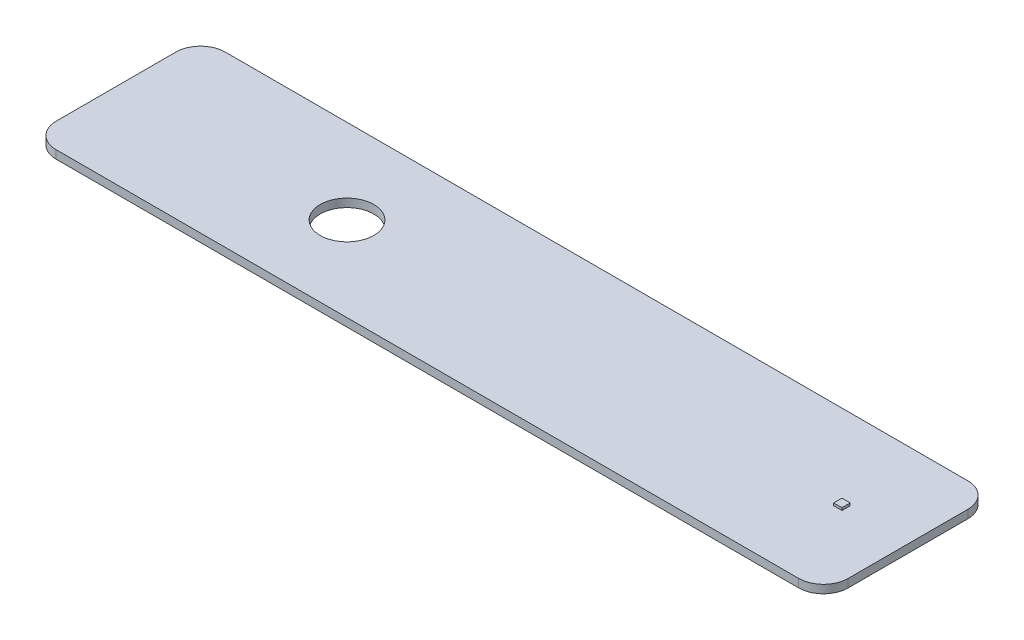
SolidWorks part; units mm, degrees
other "Markup1"
sketch "Sketch4" plane through (-48, 1.9, -10.25) normal (0, 1, 0) x (1, 0, 0)
material "Custom Plastic"
ref_plane "Front Plane" through (0, 0, 0) normal (0, 0, 1) x (1, 0, 0)
ref_plane "Top Plane" through (0, 0, 0) normal (0, 1, 0) x (1, 0, 0)
ref_plane "Right Plane" through (0, 0, 0) normal (1, 0, 0) x (0, 0, -1)
sketch "Sketch1" plane through (0, 0, 0) normal (0, 1, 0) x (1, 0, 0)
  line L1 (-45, 10.25) -> (45, 10.25)
  line L2 (-48, 7.25) -> (-48, -7.25)
  line L3 (-45, -10.25) -> (45, -10.25)
  line L4 (48, 7.25) -> (48, -7.25)
  line L5 (-48, 10.25) -> (48, -10.25) construction
  line L6 (-48, -10.25) -> (48, 10.25) construction
  arc A0 (-48, -7.25) -> (-45, -10.25) centre (-45, -7.25) ccw
  arc A1 (45, -10.25) -> (48, -7.25) centre (45, -7.25) ccw
  arc A2 (45, 10.25) -> (48, 7.25) centre (45, 7.25) cw
  arc A3 (-45, 10.25) -> (-48, 7.25) centre (-45, 7.25) ccw
  point P0 (0, 0)
  dimension "D3" = 3
  dimension "D1" = 96
  dimension "D2" = 20.5
extrude "Boss-Extrude1" add sketch "Sketch1" along normal blind 1 contours L3 A1 L4 A2 L1 A3 L2 A0
sketch "Sketch2" plane through (0, 1, 0) normal (0, 1, 0) x (1, 0, 0)
  line L1 (39.5, 0.5) -> (40.5, 0.5)
  line L2 (39.5, 0.5) -> (39.5, -0.5)
  line L3 (39.5, -0.5) -> (40.5, -0.5)
  line L4 (40.5, 0.5) -> (40.5, -0.5)
  line L5 (39.5, 0.5) -> (40.5, -0.5) construction
  line L6 (39.5, -0.5) -> (40.5, 0.5) construction
  line L7 (-48, 0) -> (48, 0) construction
  line L8 (-48, 7.25) -> (-48, -7.25) construction
  line L9 (48, 7.25) -> (48, -7.25) construction
  point P0 (40, 0)
  dimension "D1" = 1
  dimension "D2" = 1
  dimension "D3" = 88
extrude "Boss-Extrude2" add sketch "Sketch2" along normal blind 0.3 contours L3 L4 L1 L2
sketch "Sketch3" plane through (0, 1, 0) normal (0, 1, 0) x (1, 0, 0)
  line L0 (-48, 7.25) -> (-48, -7.25) construction
  line L1 (-45, -10.25) -> (45, -10.25) construction
  circle A0 centre (-20, 0) radius 3.25
  dimension "D1" = 6.5
  dimension "D2" = 28
  dimension "D3" = 10.25
extrude "Cut-Extrude1" cut sketch "Sketch3" against normal through all
